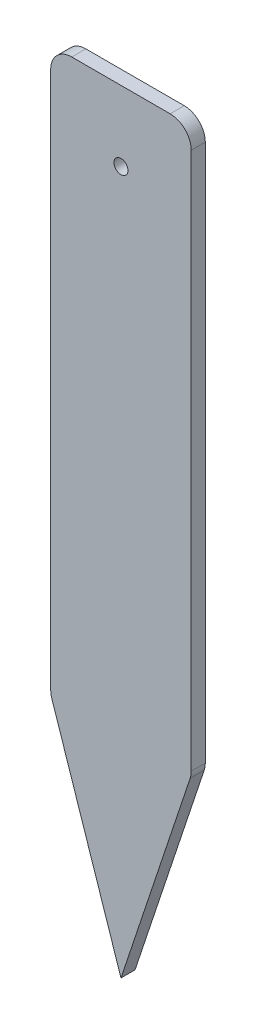
SolidWorks part; units mm, degrees
ref_plane "Спереди" through (0, 0, 0) normal (0, 0, 1) x (1, 0, 0)
ref_plane "Сверху" through (0, 0, 0) normal (0, 1, 0) x (1, 0, 0)
ref_plane "Справа" through (0, 0, 0) normal (1, 0, 0) x (0, 0, -1)
sketch "Sketch1" plane through (0, 0, 0) normal (0, 0, 1) x (1, 0, 0)
  line L0 (0, 0) -> (0, 110) construction
  line L1 (0, 0) -> (9.846, 29.5381)
  line L2 (-10, 30.4868) -> (-10, 107)
  line L3 (-7, 110) -> (7, 110)
  line L4 (10, 30.4868) -> (10, 107)
  line L5 (-9.846, 29.5381) -> (0, 0)
  circle A0 centre (0, 100) radius 1
  arc A1 (9.846, 29.5381) -> (10, 30.4868) centre (7, 30.4868) ccw
  arc A2 (-9.846, 29.5381) -> (-10, 30.4868) centre (-7, 30.4868) cw
  arc A3 (7, 110) -> (10, 107) centre (7, 107) cw
  arc A4 (-10, 107) -> (-7, 110) centre (-7, 107) cw
  point P11 (10, 30)
  point P14 (-10, 30)
  point P17 (10, 110)
  dimension "D3" = 2
  dimension "D5" = 10
  dimension "D6" = 3
  dimension "D1" = 20
  dimension "D2" = 80
  dimension "D4" = 30
extrude "Boss-Extrude1" add sketch "Sketch1" along normal blind 2
